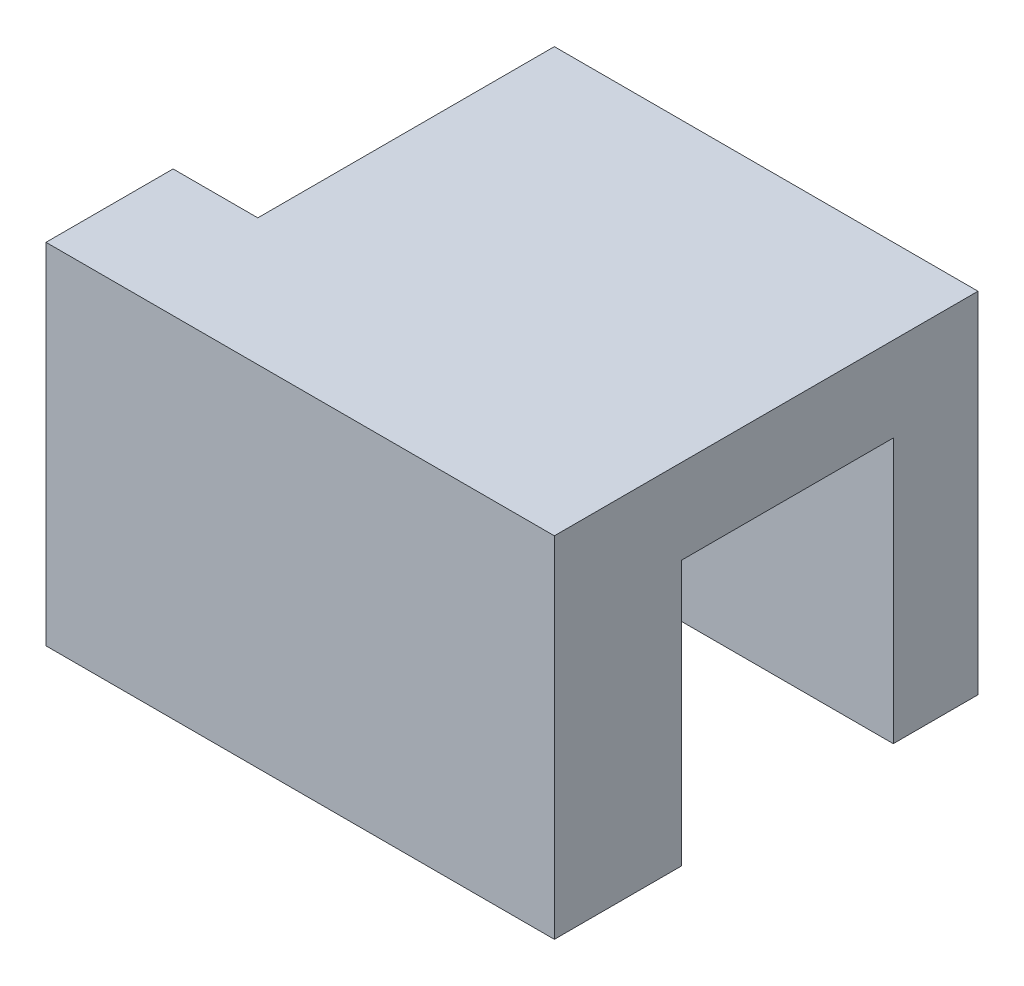
SolidWorks part; units mm, degrees
ref_plane "Front Plane" through (0, 0, 0) normal (0, 0, 1) x (1, 0, 0)
ref_plane "Top Plane" through (0, 0, 0) normal (0, 1, 0) x (1, 0, 0)
ref_plane "Right Plane" through (0, 0, 0) normal (1, 0, 0) x (0, 0, -1)
sketch "Sketch1" plane through (0, 0, 0) normal (0, 1, 0) x (1, 0, 0)
  line L0 (-2.5645, 3.2952) -> (14.4355, 3.2952)
  line L1 (-5.5645, 3.2952) -> (-4.0645, 3.2952)
  line L2 (-5.5645, 3.2952) -> (-5.5645, -2.7048)
  line L3 (-5.5645, -2.7048) -> (14.4355, -2.7048)
  line L4 (14.4355, 3.2952) -> (14.4355, -2.7048)
  line L9 (-2.5645, 3.2952) -> (-4.0645, 3.2952)
  dimension "D1" = 6
  dimension "D3" = 20
extrude "Boss-Extrude1" add sketch "Sketch1" along normal blind 12.5
sketch "Sketch2" plane through (14.4355, 0, 0) normal (1, 0, 0) x (0, 0, -1)
  line L0 (3.2952, 12.5) -> (3.2952, 0) construction
  line L1 (-2.7048, 12.5) -> (13.2952, 12.5)
  line L2 (-2.7048, 12.5) -> (-2.7048, 16.5)
  line L3 (-2.7048, 16.5) -> (17.2952, 16.5)
  line L4 (17.2952, 12.5) -> (17.2952, 16.5)
  line L6 (17.2952, 12.5) -> (17.2952, 0)
  line L7 (17.2952, 0) -> (13.2952, 0)
  line L8 (13.2952, 12.5) -> (13.2952, 0)
  line L10 (-2.7048, 0) -> (3.2952, 0) construction
  dimension "D1" = 4
  dimension "D2" = 4
  dimension "D3" = 10
extrude "Boss-Extrude4" add sketch "Sketch2" against normal blind 20
sketch "Sketch5" plane through (-5.5645, 0, 0) normal (-1, 0, 0) x (0, 0, 1)
  line L0 (-3.2952, 0) -> (2.7048, 0)
  line L1 (-3.2952, 12.5) -> (-3.2952, 0) construction
  line L2 (2.7048, 0) -> (2.7048, 16.5)
  line L3 (2.7048, 16.5) -> (-3.2952, 16.5)
  line L4 (-17.2952, 16.5) -> (2.7048, 16.5) construction
  line L5 (-3.2952, 16.5) -> (-3.2952, 11.3388)
  line L6 (-3.2952, 11.3388) -> (0.5437, 7.5)
  line L7 (0.5437, 7.5) -> (-3.2952, 3.6612)
  line L8 (-3.2952, 3.6612) -> (-3.2952, 0)
  line L10 (-8.2952, 12.5) -> (-8.2952, 7.5) construction
  line L11 (-3.2952, 12.5) -> (-13.2952, 12.5) construction
  point P15 (0, 0)
  dimension "D1" = 90
  dimension "D2" = 5
  dimension "D3" = 6.25
extrude "Boss-Extrude5" add sketch "Sketch5" along normal blind 4
sketch "Sketch3" plane through (0, 0, -17.2952) normal (0, 0, -1) x (-1, 0, 0)
  line L0 (-2.4355, 0) -> (-2.4355, 12.5) construction
  line L1 (-2.4355, 0) -> (-14.4355, 0) construction
  point P0 (-8.4355, 6.25)
  point P3 (-2.4355, 6.25)
  point P6 (-8.4355, 0)
hole_wizard "M2x0.4 Tapped Hole1" positions "3DSketch1" profile "Sketch4" tap size "M2x0.4" standard "BSI"
sketch3d "3DSketch1"
  point P0 (8.4355, 6.25, -17.2952)
sketch "Sketch4" plane through (8.4355, 6.25, -17.2952) normal (1, 0, 0) x (0, 1, 0)
  line L0 (0, 0) -> (0, 4)
  line L1 (0, 4) -> (0.8, 4)
  line L2 (0.8, 4) -> (0.8, 0)
  line L5 (0.8, 0) -> (0, 0)
  line L11 (0, -6.35) -> (0, 107.95) construction
  dimension "Thru Tap Drill Dia." = 1.6
  dimension "Thru Tap Drill Depth" = 4
cosmetic thread "Hole Thread1" parameters "D2"=2
